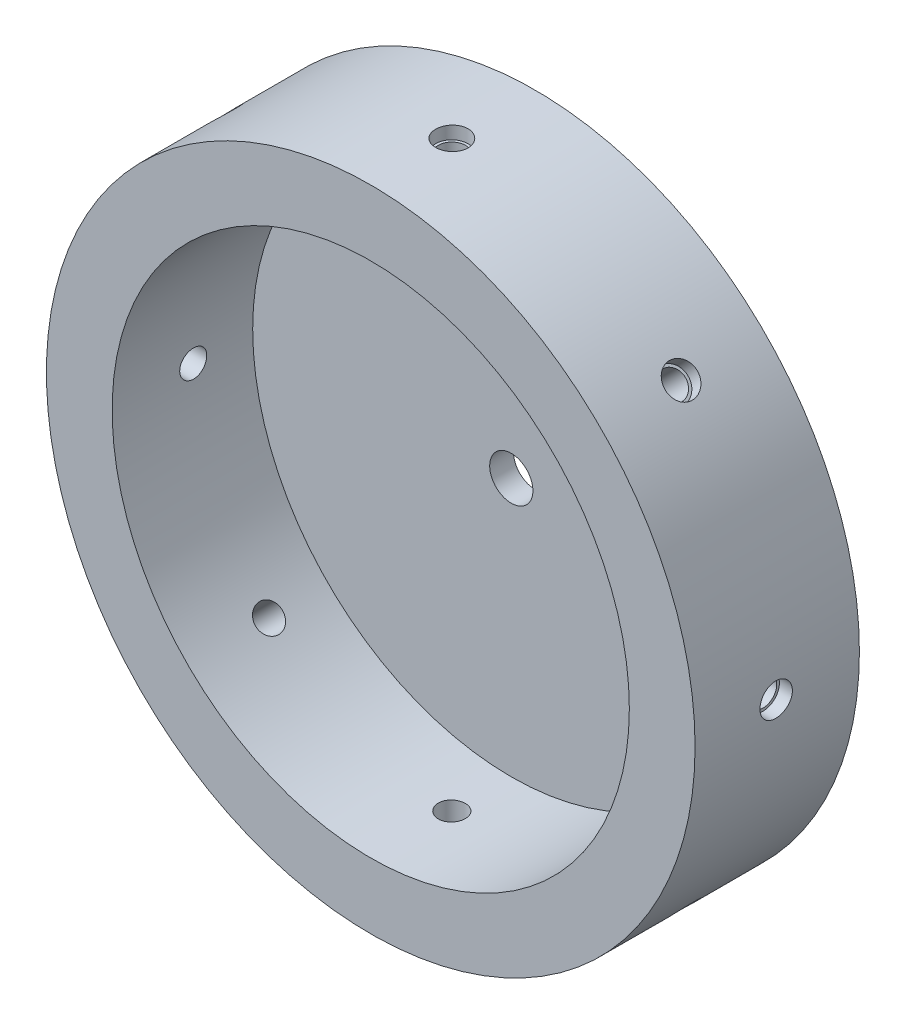
SolidWorks part; units mm, degrees
other "Markup1"
sketch "Sketch8" plane through (110, 110, 0) normal (0.0901, 0.1911, 0.9774) x (0.9758, -0.2132, -0.0483)
ref_plane "Front Plane" through (0, 0, 0) normal (0, 0, 1) x (1, 0, 0)
ref_plane "Top Plane" through (0, 0, 0) normal (0, 1, 0) x (1, 0, 0)
ref_plane "Right Plane" through (0, 0, 0) normal (1, 0, 0) x (0, 0, -1)
sketch "Sketch2" plane through (0, 0, 0) normal (0, 0, 1) x (1, 0, 0)
  circle A0 centre (0, 0) radius 150
  circle A1 centre (0, 0) radius 119.6
  dimension "D1" = 300
  dimension "D2" = 239.2
extrude "Boss-Extrude1" add sketch "Sketch2" against normal blind 75
sketch "Sketch3" plane through (0, 0, -75) normal (0, 0, -1) x (-1, 0, 0)
  circle A0 centre (0, 0) radius 150
  circle A1 centre (0, 0) radius 10
  dimension "D1" = 20
  dimension "D2" = 300
extrude "Boss-Extrude2" add sketch "Sketch3" along normal blind 1 and the other way blind 10
ref_plane "Plane1" through (0, -150, 0) normal (0, 1, 0) x (1, 0, 0)
sketch "Sketch4" plane through (0, -150, 0) normal (0, 1, 0) x (1, 0, 0)
  circle A0 centre (0, 37.5) radius 7.5
extrude "Cut-Extrude4" cut sketch "Sketch4" along normal blind 6
sketch "Sketch7" plane through (0, -144, 0) normal (0, -1, 0) x (1, 0, 0)
  circle A0 centre (0, -37.5) radius 6.25
extrude "Cut-Extrude5" cut sketch "Sketch7" against normal blind 50
pattern_circular "CirPattern1" count 8 over 360 about axis through (0, 0, 0) along (0, 0, 1) of "Cut-Extrude5", "Cut-Extrude4"
